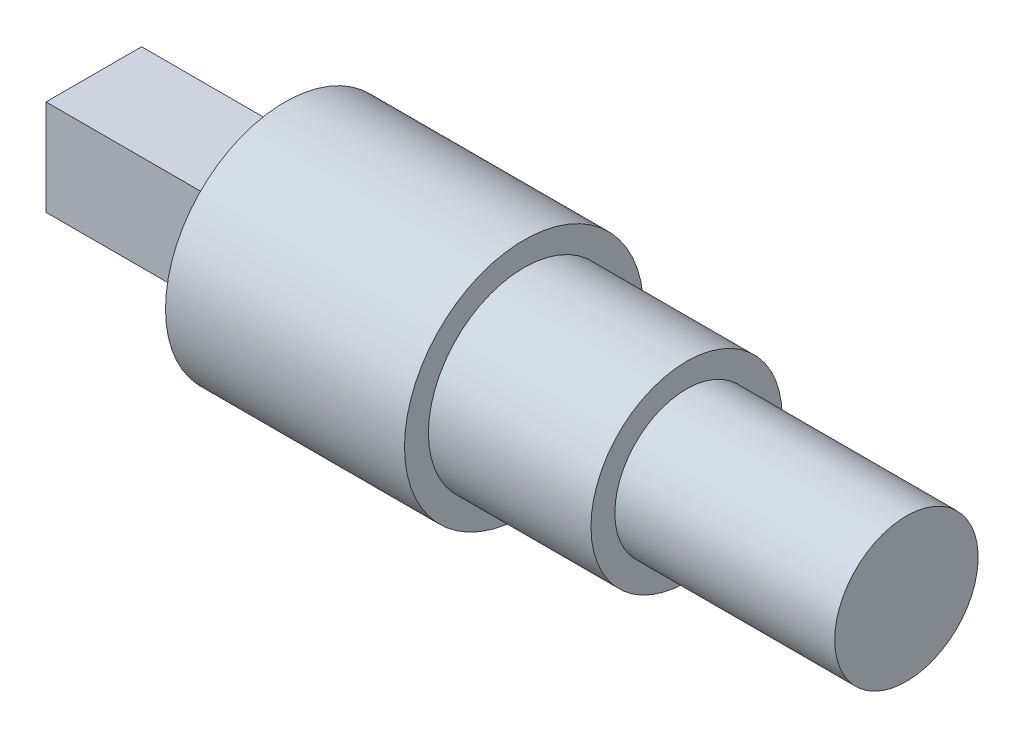
SolidWorks part; units mm, degrees
material "Сталь"
ref_plane "Спереди" through (0, 0, 0) normal (0, 0, 1) x (1, 0, 0)
ref_plane "Сверху" through (0, 0, 0) normal (0, 1, 0) x (1, 0, 0)
ref_plane "Справа" through (0, 0, 0) normal (1, 0, 0) x (0, 0, -1)
sketch "Эскиз2" plane through (0, 0, 0) normal (0, 0, 1) x (1, 0, 0)
  line L0 (0, 0) -> (89.4724, 0) construction
  line L1 (0, 0) -> (0, 5)
  line L2 (0, 5) -> (20, 5)
  line L3 (20, 5) -> (20, 12.5)
  line L4 (20, 12.5) -> (45, 12.5)
  line L5 (45, 12.5) -> (45, 10)
  line L6 (45, 10) -> (62, 10)
  line L7 (62, 10) -> (62, 7.5)
  line L8 (62, 7.5) -> (85, 7.5)
  line L9 (85, 7.5) -> (85, 0)
  line L10 (0, 0) -> (85, 0)
  dimension "D1" = 20
  dimension "D2" = 85
  dimension "D3" = 23
  dimension "D4" = 40
  dimension "D5" = 10
  dimension "D6" = 15
  dimension "D7" = 25
  dimension "D8" = 20
revolve "Повернуть1" add sketch "Эскиз2" angle 360 about L0
sketch "Эскиз3" plane through (0, 0, 0) normal (-1, 0, 0) x (0, 0, 1)
  line L1 (-5, -5) -> (5, -5)
  line L2 (-5, -5) -> (-5, 5)
  line L3 (-5, 5) -> (5, 5)
  line L4 (5, -5) -> (5, 5)
  line L5 (-5, -5) -> (5, 5) construction
  line L6 (-5, 5) -> (5, -5) construction
  circle A0 centre (0, 0) radius 5 construction
  circle A1 centre (0, 0) radius 5 construction
  point P0 (0, 0)
extrude "Бобышка-Вытянуть1" add sketch "Эскиз3" against normal up to surface (20 mm away) up to face at (20, 0, 5)
